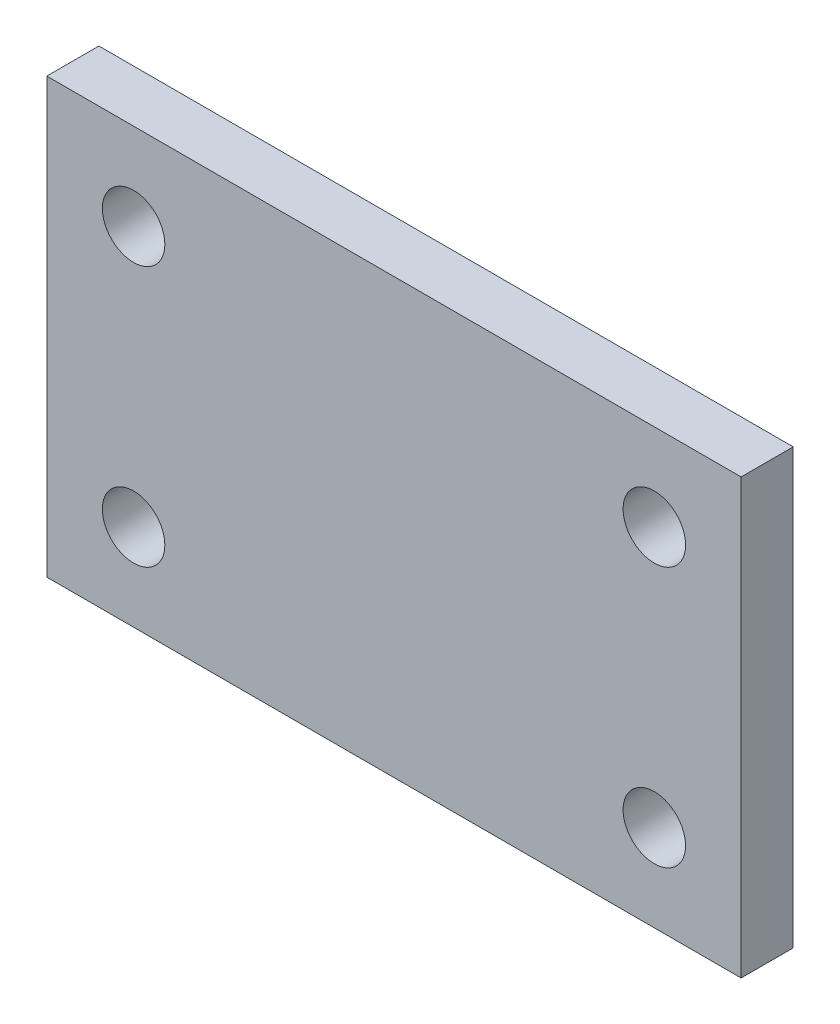
SolidWorks part; units mm, degrees
ref_plane "Plan de face" through (0, 0, 0) normal (0, 0, 1) x (1, 0, 0)
ref_plane "Plan de dessus" through (0, 0, 0) normal (0, 1, 0) x (1, 0, 0)
ref_plane "Plan de droite" through (0, 0, 0) normal (1, 0, 0) x (0, 0, -1)
sketch "Esquisse1" plane through (0, 0, 0) normal (0, 0, 1) x (1, 0, 0)
  line L1 (-15.0095, 14.5619) -> (24.9905, 14.5619)
  line L2 (-15.0095, 14.5619) -> (-15.0095, -10.4381)
  line L3 (-15.0095, -10.4381) -> (24.9905, -10.4381)
  line L4 (24.9905, 14.5619) -> (24.9905, -10.4381)
  dimension "D1" = 40
  dimension "D2" = 25
extrude "Boss.-Extru.1" add sketch "Esquisse1" along normal blind 3
sketch "Esquisse2" plane through (0, 0, 3) normal (0, 0, 1) x (1, 0, 0)
  line L0 (4.9905, 14.5619) -> (4.9905, 9.5619) construction
  line L3 (4.9905, -5.4381) -> (-10.0095, -5.4381) construction
  line L4 (4.9905, -5.4381) -> (19.9905, -5.4381) construction
  line L5 (24.9905, 14.5619) -> (-15.0095, 14.5619) construction
  line L6 (4.9905, 9.5619) -> (4.9905, -5.4381) construction
  line L7 (4.9905, 9.5619) -> (19.9905, 9.5619) construction
  line L8 (4.9905, 9.5619) -> (-10.0095, 9.5619) construction
  line L9 (-10.0095, 9.5619) -> (-10.0095, -5.4381) construction
  line L10 (19.9905, 9.5619) -> (19.9905, -5.4381) construction
  point P5 (-10.0095, 9.5619)
  point P7 (-10.0095, -5.4381)
  point P8 (19.9905, 9.5619)
  point P9 (19.9905, -5.4381)
  point P16 (-10.0095, -5.4381)
  point P18 (-10.0095, 9.5619)
  point P24 (19.9905, -5.4381)
  point P26 (19.9905, 9.5619)
  dimension "D1" = 5
  dimension "D2" = 15
  dimension "D3" = 15
  dimension "D4" = 15
hole_wizard "Dégagement M33" positions "Esquisse2" profile "Esquisse3" hole size "M3" standard "ISO" end condition through all
sketch "Esquisse3" plane through (19.9905, 9.5619, 3) normal (1, 0, 0) x (0, -1, 0)
  line L0 (0, 0) -> (0, 3)
  line L1 (0, 3) -> (1.8, 3)
  line L2 (1.8, 3) -> (1.8, 0)
  line L5 (1.8, 0) -> (0, 0)
  line L11 (0, -6.35) -> (0, 107.95) construction
  dimension "Diamètre du perçage jusqu'au prochain" = 3.6
  dimension "Profondeur du perçage jusqu'au prochain" = 3
